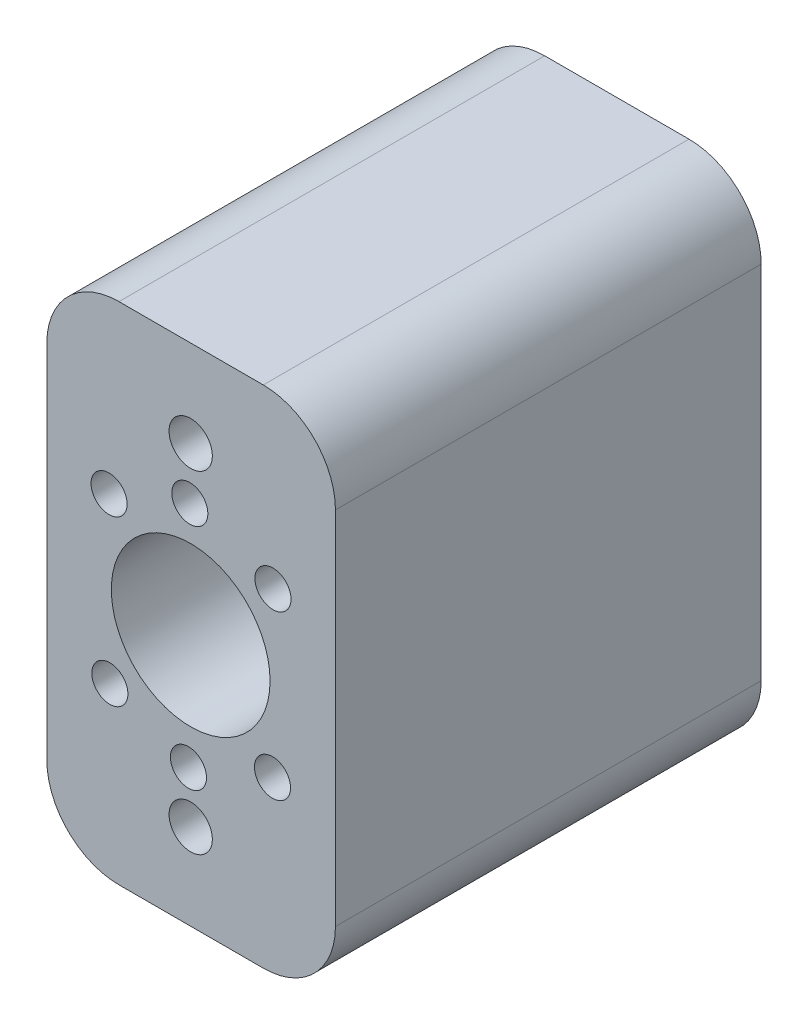
SolidWorks part; units mm, degrees
ref_plane "Front Plane" through (0, 0, 0) normal (0, 0, 1) x (1, 0, 0)
ref_plane "Top Plane" through (0, 0, 0) normal (0, 1, 0) x (1, 0, 0)
ref_plane "Right Plane" through (0, 0, 0) normal (1, 0, 0) x (0, 0, -1)
sketch "Sketch1" plane through (0, 0, 0) normal (0, 0, 1) x (1, 0, 0)
  line L0 (0.0608, 20.3128) -> (0.0608, -20.1872) construction
  line L1 (-14.9392, 0.0628) -> (15.0608, 0.0628) construction
  line L2 (-14.9392, 13.6666) -> (-14.9392, -13.541)
  line L3 (15.0608, 13.6666) -> (15.0608, -13.541)
  line L4 (0.0608, 20.3128) -> (0.0608, 35.0628) construction
  line L5 (-19.9392, 35.0628) -> (20.0608, 35.0628)
  line L6 (-19.9392, 35.0628) -> (-19.9392, -34.9372)
  line L7 (-19.9392, -34.9372) -> (20.0608, -34.9372)
  line L8 (20.0608, 35.0628) -> (20.0608, -34.9372)
  line L9 (-19.9392, 35.0628) -> (20.0608, -34.9372) construction
  line L10 (-19.9392, -34.9372) -> (20.0608, 35.0628) construction
  line L11 (0.0608, 0.0628) -> (20.0608, 0.0628) construction
  arc A0 (-14.9392, -13.541) -> (15.0608, -13.541) centre (0.0608, 0.0628) ccw
  arc A1 (15.0608, 13.6666) -> (-14.9392, 13.6666) centre (0.0608, 0.0628) ccw
  dimension "D1" = 40.5
  dimension "D2" = 30
  dimension "D3" = 20
  dimension "D4" = 35
sketch "Sketch2" plane through (0, 0, 0) normal (0, 0, 1) x (1, 0, 0)
  line L0 (0, -20.25) -> (0, 20.25) construction
  line L2 (15, 0) -> (-15, 0) construction
  line L6 (0, 0) -> (11.3137, -11.3137) construction
  circle A2 centre (0, 0) radius 11
  circle A3 centre (-11.3137, 11.3137) radius 2.5
  circle A4 centre (-0.1223, 15.7597) radius 2.5
  circle A5 centre (11.4027, 11.2637) radius 2.5
  circle A6 centre (11.3394, -11.4064) radius 2.5
  circle A7 centre (-0.3123, -16.0291) radius 2.5
  circle A8 centre (-11.2041, -11.4064) radius 2.5
  point P0 (0, -16)
  point P2 (11.3137, -11.3137)
  point P30 (-11.3137, -11.3137)
  point P32 (-11.3137, 11.3137)
  point P33 (0, 16)
  point P34 (11.3137, 11.3137)
  dimension "D2" = 45
  dimension "D3" = 16
extrude "Boss-Extrude1" add sketch "Sketch1" along normal blind 59 contours L5 L8 L7 L6
extrude "Cut-Extrude1" cut sketch "Sketch2" along normal through all
sketch "Sketch5" plane through (-19.9392, 0, 0) normal (-1, 0, 0) x (0, 0, 1)
  line L0 (63.3059, 0.0628) -> (-4.3059, 0.0628) construction
  line L2 (29.5, 35.0628) -> (29.5, -34.9372) construction
  line L5 (29.5, 35.0628) -> (29.5, -34.9372) construction
  line L6 (59, 35.0628) -> (0, 35.0628) construction
  line L7 (59, -34.9372) -> (0, -34.9372) construction
  line L8 (0, 0.0628) -> (59, 0.0628) construction
  line L9 (0, 35.0628) -> (0, -34.9372) construction
  line L10 (59, 35.0628) -> (59, -34.9372) construction
  line L13 (14.5, 15.0628) -> (44.5, 15.0628)
  line L14 (14.5, 15.0628) -> (14.5, -14.9372)
  line L15 (14.5, -14.9372) -> (44.5, -14.9372)
  line L16 (44.5, 15.0628) -> (44.5, -14.9372)
  line L17 (14.5, 15.0628) -> (44.5, -14.9372) construction
  line L18 (14.5, -14.9372) -> (44.5, 15.0628) construction
  line L19 (17.5, -11.9372) -> (41.5, -11.9372)
  line L20 (17.5, -11.9372) -> (17.5, -17.9372)
  line L21 (17.5, -17.9372) -> (41.5, -17.9372)
  line L22 (41.5, -11.9372) -> (41.5, -17.9372)
  line L23 (17.5, -11.9372) -> (41.5, -17.9372) construction
  line L24 (17.5, -17.9372) -> (41.5, -11.9372) construction
  circle A0 centre (44.5, 15.0628) radius 1.25
  circle A1 centre (44.5, -14.9372) radius 1.25
  circle A2 centre (14.5, -14.9372) radius 1.25
  circle A3 centre (14.5, 15.0628) radius 1.25
  point P2 (29.5, 0.0628)
  point P16 (29.5, -14.9372)
  dimension "D1" = 30
  dimension "D3" = 6
  dimension "D2" = 30
  dimension "D4" = 24
hole_wizard "Ø2.5 (2.5) Diameter Hole1" positions "Sketch7" profile "Sketch8" hole size "Ø2.5" standard "ANSI Metric"
sketch "Sketch7" plane through (-19.9392, 0, 0) normal (-1, 0, 0) x (0, 0, 1)
  point P0 (14.5, 15.0628)
  point P3 (44.5, 15.0628)
  point P6 (44.5, -14.9372)
  point P9 (14.5, -14.9372)
sketch "Sketch8" plane through (-19.9392, 15.0628, 14.5) normal (0, 1, 0) x (0, 0, 1)
  line L0 (0, 0) -> (0, 8)
  line L1 (0, 8) -> (1.25, 7.2489)
  line L2 (1.25, 7.2489) -> (1.25, 0)
  line L5 (1.25, 0) -> (0, 0)
  line L10 (0, 8) -> (-1.25, 7.2489) construction
  line L11 (0, -6.35) -> (0, 107.95) construction
  dimension "Hole Dia." = 2.5
  dimension "Hole Depth" = 8
  dimension "Drill Angle" = 118
extrude "Cut-Extrude2" cut sketch "Sketch5" against normal blind 3 contours L19 L22 L21 L20
fillet "Fillet2" radius 10 1 edges at (20.0608, 35.0628, 29.5)
fillet "Fillet3" radius 10 1 edges at (-19.9392, 35.0628, 29.5)
fillet "Fillet4" radius 10 1 edges at (20.0608, -34.9372, 29.5)
fillet "Fillet5" radius 10 1 edges at (-19.9392, -34.9372, 29.5)
sketch "Sketch9" plane through (0, 0, 59) normal (0, 0, 1) x (1, 0, 0)
  circle A0 centre (0, 23.01) radius 3
  circle A1 centre (0, 0) radius 11 construction
  circle A2 centre (0, -23.01) radius 3
  dimension "D1" = 23.01
  dimension "D2" = 23.01
extrude "Cut-Extrude3" cut sketch "Sketch9" against normal through all
